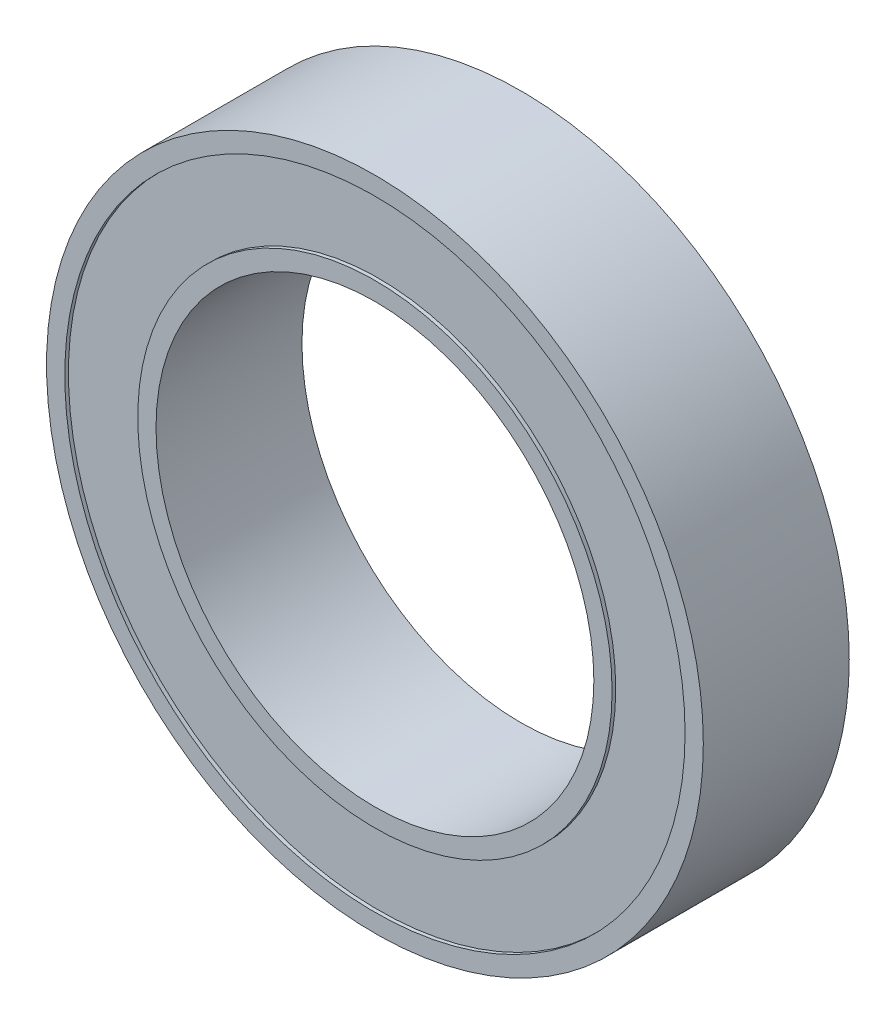
SolidWorks part; units mm, degrees
ref_plane "Front Plane" through (0, 0, 0) normal (0, 0, 1) x (1, 0, 0)
ref_plane "Top Plane" through (0, 0, 0) normal (0, 1, 0) x (1, 0, 0)
ref_plane "Right Plane" through (0, 0, 0) normal (1, 0, 0) x (0, 0, -1)
sketch "Sketch1" plane through (0, 0, 0) normal (0, 0, 1) x (1, 0, 0)
  circle A0 centre (0, 0) radius 9
  circle A1 centre (0, 0) radius 6
  dimension "D1" = 18
  dimension "D2" = 12
extrude "Boss-Extrude1" add sketch "Sketch1" along normal blind 4
sketch "Sketch2" plane through (0, 0, 0) normal (0, 0, -1) x (-1, 0, 0)
  circle A0 centre (0, 0) radius 6.5
  circle A1 centre (0, 0) radius 8.5
  dimension "D1" = 17
  dimension "D2" = 13
extrude "Cut-Extrude1" cut sketch "Sketch2" against normal blind 0.1
sketch "Sketch3" plane through (0, 0, 4) normal (0, 0, 1) x (1, 0, 0)
  circle A1 centre (0, 0) radius 8.5
  circle A2 centre (0, 0) radius 8.5
  circle A3 centre (0, 0) radius 6.5
  circle A4 centre (0, 0) radius 6.5
  dimension "D1" = 0
  dimension "D2" = 0
extrude "Cut-Extrude2" cut sketch "Sketch3" against normal blind 0.1
equation "\"I\"= 12mm"
equation "\"E\"= 18mm"
equation "\"T\"= 4mm"
equation "\"D1@Sketch1\"=\"E\""
equation "\"D2@Sketch1\"=\"I\""
equation "\"D1@Sketch2\"=\"E\"-1"
equation "\"D2@Sketch2\"=\"I\"+1"
equation "\"D1@Boss-Extrude1\"=\"T\""
